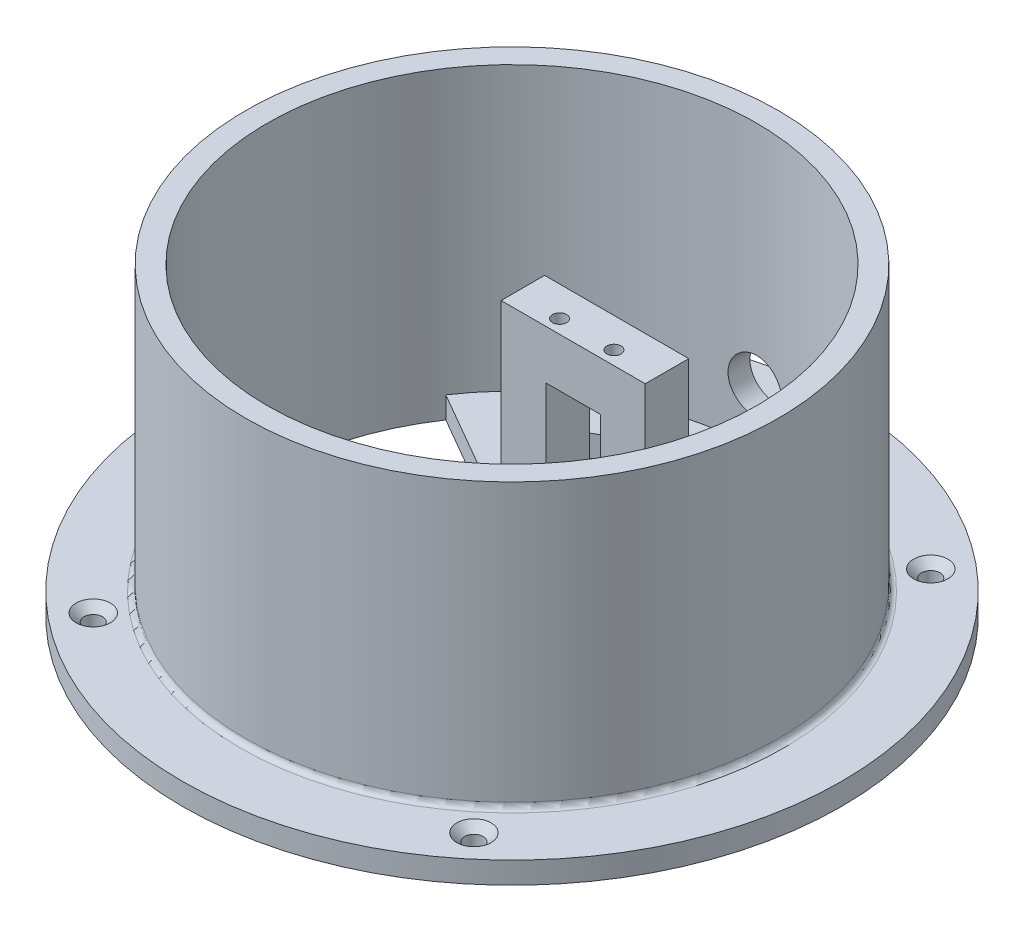
SolidWorks part; units mm, degrees
ref_plane "Front Plane" through (0, 0, 0) normal (0, 0, 1) x (1, 0, 0)
ref_plane "Top Plane" through (0, 0, 0) normal (0, 1, 0) x (1, 0, 0)
ref_plane "Right Plane" through (0, 0, 0) normal (1, 0, 0) x (0, 0, -1)
sketch "Sketch1" plane through (0, 0, 0) normal (0, 1, 0) x (1, 0, 0)
  circle A0 centre (0, 0) radius 60.625
  circle A1 centre (0, 0) radius 45
  dimension "D1" = 121.25
  dimension "D2" = 90
extrude "Boss-Extrude1" add sketch "Sketch1" along normal blind 4
sketch "Sketch2" plane through (0, 4, 0) normal (0, 1, 0) x (1, 0, 0)
  circle A0 centre (0, 0) radius 45 construction
  circle A1 centre (0, 0) radius 45
  circle A2 centre (0, 0) radius 49
  dimension "D1" = 4
extrude "Boss-Extrude2" add sketch "Sketch2" along normal blind 52
sketch "Sketch3" plane through (0, 0, 0) normal (1, 0, 0) x (0, 0, -1)
  line L0 (-46.75, 30) -> (-31.75, 30)
  line L1 (-31.75, 30) -> (-31.75, 38)
  line L2 (-31.75, 38) -> (-46.75, 38)
  line L3 (-46.75, 38) -> (-46.75, 30)
  line L4 (-45, 56) -> (-45, 0)
  line L5 (-31.75, 38) -> (-45, 24.75)
  line L6 (-45, 0) -> (45, 0) construction
  line L7 (11.25, 38) -> (19.25, 38)
  line L8 (11.25, 38) -> (11.25, 0)
  line L9 (11.25, 0) -> (19.25, 0)
  line L10 (19.25, 38) -> (19.25, 0)
  line L11 (11.25, 38) -> (19.25, 0) construction
  line L12 (11.25, 0) -> (19.25, 38) construction
  line L13 (49, 56) -> (-49, 56) construction
  line L14 (45, 56) -> (-45, 56) construction
  point P8 (15.25, 19)
  dimension "D1" = 8
  dimension "D2" = 18
  dimension "D3" = 11.25
  dimension "D4" = 43
  dimension "D5" = 15
  dimension "D6" = 45
  dimension "D7" = 8
  dimension "D8" = 18
extrude "Boss-Extrude3" add sketch "Sketch3" along normal mid plane 26.5 contours L10 L7 L8 L9 | L5 L2 L4 L0 | L5 L0 L4 | L1 L5 L0
sketch "Sketch6" plane through (0, 0, -11.25) normal (0, 0, 1) x (1, 0, 0)
  line L0 (13.25, 38) -> (-13.25, 38) construction
  line L5 (-5, 29) -> (5, 29)
  line L6 (-5, 29) -> (-5, 5)
  line L7 (-5, 5) -> (5, 5)
  line L8 (5, 29) -> (5, 5)
  line L9 (-5, 29) -> (5, 5) construction
  line L10 (-5, 5) -> (5, 29) construction
  point P0 (0, 17)
  point P8 (0, 5)
  dimension "D1" = 10
  dimension "D2" = 9
  dimension "D3" = 5
extrude "Cut-Extrude1" cut sketch "Sketch6" against normal blind 26
sketch "Sketch7" plane through (0, 0, -11.25) normal (0, 0, 1) x (1, 0, 0)
  line L0 (0, 56) -> (0, 0) construction
  circle A0 centre (0, 14) radius 5
  dimension "D1" = 10
  dimension "D2" = 14
extrude "Cut-Extrude2" cut sketch "Sketch7" against normal blind 58
sketch "Sketch8" plane through (0, 38, 0) normal (0, 1, 0) x (1, 0, 0)
  line L0 (-5, 13.75) -> (5, 13.75) construction
  line L1 (-5, -34.25) -> (5, -34.25) construction
  line L2 (13.25, -31.75) -> (-13.25, -31.75) construction
  circle A0 centre (-5, 13.75) radius 1.3
  circle A1 centre (5, 13.75) radius 1.3
  circle A2 centre (-5, -34.25) radius 1.3
  circle A3 centre (5, -34.25) radius 1.3
  dimension "D1" = 2.6
  dimension "D2" = 5
  dimension "D3" = 10
  dimension "D4" = 10
  dimension "D5" = 2.5
  dimension "D6" = 48
extrude "Cut-Extrude3" cut sketch "Sketch8" against normal blind 7.2
sketch "Sketch9" plane through (0, 0, 0) normal (0, -1, 0) x (1, 0, 0)
  line L0 (13.25, -11.25) -> (-13.25, -11.25) construction
  line L1 (13.25, -11.25) -> (-13.25, -11.25)
  line L2 (-13.25, -11.25) -> (-37.3186, -25.146)
  line L3 (0, 0) -> (0, -24.2081) construction
  line L4 (13.25, -11.25) -> (37.3186, -25.146)
  line L6 (-19.7667, -24.25) -> (-25.0033, -27.2734)
  line L7 (19.7667, -24.25) -> (25.0033, -27.2734)
  line L8 (-19.7667, -24.25) -> (19.7667, -24.25)
  line L9 (-11.1064, -19.25) -> (-25.0033, -27.2734) construction
  line L10 (11.1064, -19.25) -> (-11.1064, -19.25) construction
  line L11 (11.1064, -19.25) -> (25.0033, -27.2734) construction
  line L12 (13.25, -19.25) -> (-13.25, -19.25) construction
  circle A0 centre (0, 0) radius 45 construction
  arc A1 (-37.3186, -25.146) -> (37.3186, -25.146) centre (0, 0) ccw
  arc A2 (-25.0033, -27.2734) -> (25.0033, -27.2734) centre (0, 0) ccw
  dimension "D1" = 60
  dimension "D3" = 5
  dimension "D2" = 8
extrude "Boss-Extrude4" add sketch "Sketch9" against normal blind 4
sketch "Sketch10" plane through (0, 4, 0) normal (0, 1, 0) x (1, 0, 0)
  line L1 (-35, -42) -> (35, -42) construction
  line L2 (-35, -42) -> (-35, 42) construction
  line L3 (-35, 42) -> (35, 42) construction
  line L4 (35, -42) -> (35, 42) construction
  line L5 (-35, -42) -> (35, 42) construction
  line L6 (-35, 42) -> (35, -42) construction
  point P0 (0, 0)
  dimension "D1" = 84
  dimension "D2" = 70
hole_wizard "CSK for M3 Countersunk Flat Head Screw1" positions "Sketch11" profile "Sketch12" countersink size "M3" standard "DIN"
sketch "Sketch11" plane through (0, 4, 0) normal (0, 1, 0) x (1, 0, 0)
  point P0 (-35, 42)
  point P3 (35, 42)
  point P6 (35, -42)
  point P9 (-35, -42)
sketch "Sketch12" plane through (-35, 4, -42) normal (1, 0, 0) x (0, 0, 1)
  line L0 (0, 0) -> (0, 5.0215)
  line L1 (0, 5.0215) -> (1.7, 4)
  line L2 (1.7, 4) -> (1.7, 1.45)
  line L3 (1.7, 1.45) -> (3.15, 0)
  line L5 (3.15, 0) -> (0, 0)
  line L6 (-1.7, 1.45) -> (-3.15, 0) construction
  line L10 (0, 5.0215) -> (-1.7, 4) construction
  line L11 (0, -6.35) -> (0, 107.95) construction
  dimension "Hole Dia." = 3.4
  dimension "Hole Depth" = 4
  dimension "Near C'Sink Dia." = 6.3
  dimension "Near C'Sink Angle" = 90
  dimension "Drill Angle" = 118
fillet "Fillet1" radius 1 1 edges at (0, 4, 49)
